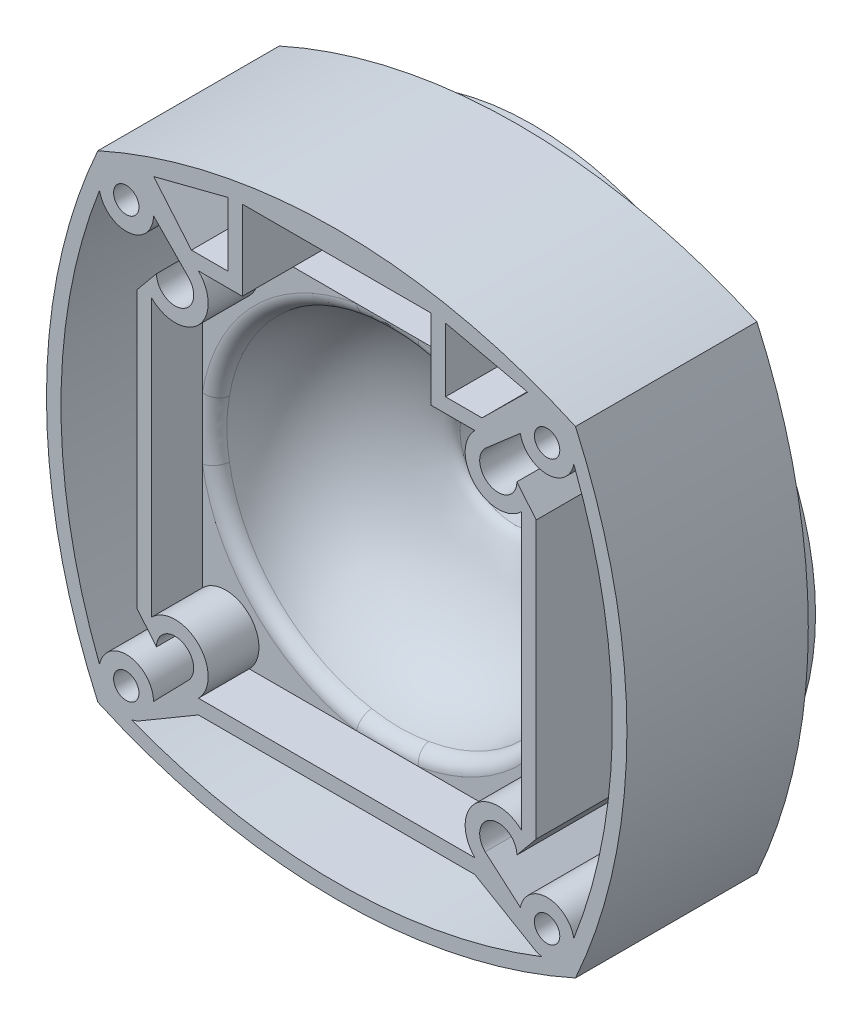
SolidWorks part; units mm, degrees
ref_plane "前视基准面" through (0, 0, 0) normal (0, 0, 1) x (1, 0, 0)
ref_plane "上视基准面" through (0, 0, 0) normal (0, 1, 0) x (1, 0, 0)
ref_plane "右视基准面" through (0, 0, 0) normal (1, 0, 0) x (0, 0, -1)
sketch "草图2" plane through (0, 0, 0) normal (0, 0, 1) x (1, 0, 0)
  line L0 (25.5, 25.5) -> (-25.5, 25.5)
  line L1 (-25.5, 25.5) -> (-25.5, -25.5)
  line L2 (-25.5, -25.5) -> (25.5, -25.5)
  line L3 (25.5, -25.5) -> (25.5, 25.5)
  circle A0 centre (29, -29) radius 1.4
  circle A1 centre (-29, 29) radius 1.4
  circle A2 centre (29, 29) radius 1.4
  circle A3 centre (-29, -29) radius 1.4
  circle A4 centre (-22.2739, -22.2739) radius 3
  circle A5 centre (22.2739, -22.2739) radius 3
  circle A6 centre (-22.2739, 22.2739) radius 3
  circle A7 centre (22.2739, 22.2739) radius 3
  circle A8 centre (-22.2739, -22.2739) radius 1.75
  circle A9 centre (22.2739, -22.2739) radius 1.75
  circle A10 centre (22.2739, 22.2739) radius 1.75
  circle A11 centre (-22.2739, 22.2739) radius 1.75
  arc A12 (32.915, 32.915) -> (-32.915, 32.915) centre (0, -40) ccw
  arc A13 (32.915, -32.915) -> (32.915, 32.915) centre (-40, 0) ccw
  arc A14 (-32.915, -32.915) -> (32.915, -32.915) centre (0, 40) ccw
  arc A15 (-32.915, 32.915) -> (-32.915, -32.915) centre (40, 0) ccw
  arc A16 (0, 25.5) -> (25.5, 0) centre (0, 0) ccw
sketch "草图3" plane through (0, 0, 0) normal (0, 0, 1) x (1, 0, 0)
  arc A8 (-32.915, -32.915) -> (32.915, -32.915) centre (0, 40) ccw
  arc A9 (32.915, -32.915) -> (32.915, 32.915) centre (-40, 0) ccw
  arc A10 (32.915, 32.915) -> (-32.915, 32.915) centre (0, -40) ccw
  arc A11 (-32.915, 32.915) -> (-32.915, -32.915) centre (40, 0) ccw
  arc A12 (-32.915, -32.915) -> (32.915, -32.915) centre (0, 40) ccw
  arc A13 (32.915, -32.915) -> (32.915, 32.915) centre (-40, 0) ccw
  arc A14 (32.915, 32.915) -> (-32.915, 32.915) centre (0, -40) ccw
  arc A15 (-32.915, 32.915) -> (-32.915, -32.915) centre (40, 0) ccw
  dimension "D1" = 0
extrude "凸台-拉伸1" add sketch "草图3" along normal blind 25
sketch "草图4" plane through (0, 0, 0) normal (0, 1, 0) x (1, 0, 0)
  line L0 (0, 0) -> (0, -50000) construction
  line L1 (-32.915, 0) -> (32.915, 0) construction
  line L2 (0, 0) -> (7.5, 0)
  line L3 (0, -18) -> (24, -18)
  line L5 (0, -18) -> (0, 0)
  line L6 (-32.915, -25) -> (32.915, -25) construction
  line L7 (7.5, 0) -> (7.5, -0.5)
  spline S0 degree 3 poles (24, -18) (23.8657, -12.9165) (19.8494, -5.3499) (10.1514, -2.3556) (8.0632, -1.4096) (7.5337, -0.888) (7.5, -0.5) knots 0 0 0 0 0.443597 0.828919 0.884559 1 1 1 1
  point P4 (0, 0)
  dimension "D1" = 7.5
  dimension "D2" = 24
  dimension "D3" = 7
  dimension "D4" = 0.5
revolve "切除-旋转1" cut sketch "草图4" angle 360 about L0
sketch "草图5" plane through (0, 0, 25) normal (0, 0, 1) x (1, 0, 0)
  line L1 (-25.5, 25.5) -> (25.5, 25.5)
  line L2 (-25.5, 25.5) -> (-25.5, -25.5)
  line L3 (-25.5, -25.5) -> (25.5, -25.5)
  line L4 (25.5, 25.5) -> (25.5, -25.5)
extrude "切除-拉伸1" cut sketch "草图5" against normal blind 7
fillet "圆角1" radius 2 1 edges at (-24, 0, 18)
sketch "草图6" plane through (0, 0, 0) normal (0, 0, -1) x (-1, 0, 0)
  circle A0 centre (29, 29) radius 3
  circle A1 centre (-29, 29) radius 3
  circle A2 centre (-29, -29) radius 3
  circle A3 centre (29, -29) radius 3
  dimension "D1" = 6
extrude "切除-拉伸2" cut sketch "草图6" against normal blind 2
sketch "草图7" plane through (0, 0, 2) normal (0, 0, -1) x (-1, 0, 0)
  circle A0 centre (29, 29) radius 1.75
  circle A1 centre (29, -29) radius 1.75
  circle A2 centre (-29, 29) radius 1.75
  circle A3 centre (-29, -29) radius 1.75
  dimension "D1" = 3.5
extrude "切除-拉伸3" cut sketch "草图7" against normal blind 43
sketch "草图8" plane through (0, 0, 18) normal (0, 0, 1) x (1, 0, 0)
  circle A0 centre (-22.2739, -22.2739) radius 4.5624
  circle A1 centre (22.2739, 22.2739) radius 4.5624
extrude "凸台-拉伸2" add sketch "草图8" along normal up to surface (7 mm away) up to face at (-27.25, -29, 25)
sketch "草图9" plane through (0, 0, 18) normal (0, 0, 1) x (1, 0, 0)
  circle A0 centre (22.2739, -22.2739) radius 4.5624
  circle A1 centre (-22.2739, 22.2739) radius 4.5624
extrude "凸台-拉伸3" add sketch "草图9" along normal up to surface (7 mm away) up to face at (-27.25, -29, 25)
sketch "草图10" plane through (0, 0, 0) normal (0, 0, -1) x (-1, 0, 0)
  circle A0 centre (0, 0) radius 11
  dimension "D1" = 22
extrude "凸台-拉伸4" add sketch "草图10" along normal blind 20
sketch "草图11" plane through (0, 0, -20) normal (0, 0, -1) x (-1, 0, 0)
  circle A0 centre (0, 0) radius 7.5
extrude "切除-拉伸4" cut sketch "草图11" against normal blind 54
sketch "草图13" plane through (0, 0, 0) normal (0, 0, -1) x (-1, 0, 0)
  line L0 (0, 0) -> (-49208.2001, 8863.0154) construction
  line L1 (0, 0) -> (-34030.5375, 36632.2606) construction
  line L2 (0, 0) -> (8863.0154, 49208.2001) construction
  line L3 (0, 0) -> (36632.2606, 34030.5375) construction
  line L4 (-17.715, 3.1907) -> (-14.7625, 2.6589)
  line L5 (-12.251, 13.1876) -> (-10.2092, 10.9897)
  line L6 (10.2092, -10.9897) -> (12.251, -13.1876)
  line L7 (14.7625, -2.6589) -> (17.715, -3.1907)
  line L8 (2.6589, 14.7625) -> (3.1907, 17.715)
  line L9 (10.9897, 10.2092) -> (13.1876, 12.251)
  line L10 (-3.1907, -17.715) -> (-2.6589, -14.7625)
  line L11 (-13.1876, -12.251) -> (-10.9897, -10.2092)
  arc A0 (-17.715, 3.1907) -> (-13.1876, -12.251) centre (0, 0) ccw
  arc A1 (-14.7625, 2.6589) -> (-10.9897, -10.2092) centre (0, 0) ccw
  circle A2 centre (0, 0) radius 11 construction
  arc A3 (17.715, -3.1907) -> (13.1876, 12.251) centre (0, 0) ccw
  arc A4 (14.7625, -2.6589) -> (10.9897, 10.2092) centre (0, 0) ccw
  arc A5 (2.6589, 14.7625) -> (-10.2092, 10.9897) centre (0, 0) ccw
  arc A6 (3.1907, 17.715) -> (-12.251, 13.1876) centre (0, 0) ccw
  arc A7 (-3.1907, -17.715) -> (12.251, -13.1876) centre (0, 0) ccw
  arc A8 (-2.6589, -14.7625) -> (10.2092, -10.9897) centre (0, 0) ccw
  dimension "D1" = 3
  dimension "D2" = 4
extrude "凸台-拉伸5" add sketch "草图13" along normal blind 15
sketch "草图14" plane through (0, 0, 0) normal (0, 0, -1) x (-1, 0, 0)
  line L0 (0.6319, -1.5445) -> (18932.2741, -46278.8923) construction
  line L1 (0, 0) -> (41074.2951, -28511.4413) construction
  line L2 (0, 0) -> (-28511.4413, -41074.2951) construction
  line L3 (0, 0) -> (46277.3478, 18931.6423) construction
  line L4 (9.4658, -23.1387) -> (8.3299, -20.362)
  line L5 (20.5137, -14.2894) -> (18.0727, -12.545)
  line L6 (-20.5371, 14.2557) -> (-18.0727, 12.545)
  line L7 (-8.3299, 20.362) -> (-9.4658, 23.1387)
  line L8 (-14.2557, -20.5371) -> (-12.545, -18.0727)
  line L9 (-23.1192, -9.5132) -> (-20.362, -8.3299)
  line L10 (20.362, 8.3299) -> (23.1387, 9.4658)
  line L11 (12.5505, 18.0689) -> (14.262, 20.5328)
  arc A0 (20.5137, -14.2894) -> (23.1387, 9.4658) centre (0, 0) ccw
  arc A1 (18.0727, -12.545) -> (20.362, 8.3299) centre (0, 0) ccw
  circle A2 centre (0, 0) radius 18 construction
  arc A3 (-18.0727, 12.545) -> (-20.362, -8.3299) centre (0, 0) ccw
  arc A4 (-20.5371, 14.2557) -> (-23.1192, -9.5132) centre (0, 0) ccw
  arc A5 (-14.2557, -20.5371) -> (9.4658, -23.1387) centre (0, 0) ccw
  arc A6 (-12.545, -18.0727) -> (8.3299, -20.362) centre (0, 0) ccw
  arc A7 (12.5505, 18.0689) -> (-8.3299, 20.362) centre (0, 0) ccw
  arc A8 (14.262, 20.5328) -> (-9.4658, 23.1387) centre (0, 0) ccw
  dimension "D1" = 3
  dimension "D2" = 4
extrude "凸台-拉伸6" add sketch "草图14" along normal blind 10
sketch "草图15" plane through (0, 0, 0) normal (0, 0, -1) x (-1, 0, 0)
  line L0 (0, 0) -> (-49831.9637, -4095.7778) construction
  line L1 (0, 0) -> (-4095.7778, 49831.9637) construction
  line L2 (0, 0) -> (-42320.3341, 26626.8534) construction
  line L3 (0, 0) -> (-26626.8534, -42320.3341) construction
  line L4 (-31.8925, -2.6213) -> (-28.9025, -2.3756)
  line L5 (-27.085, 17.0412) -> (-24.5458, 15.4436)
  line L6 (24.5458, -15.4436) -> (27.085, -17.0412)
  line L7 (31.8925, 2.6213) -> (28.9025, 2.3756)
  line L8 (-2.3756, 28.9025) -> (-2.6213, 31.8925)
  line L9 (15.4436, 24.5458) -> (17.0412, 27.085)
  line L10 (2.6213, -31.8925) -> (2.3756, -28.9025)
  line L11 (-17.0412, -27.085) -> (-15.4436, -24.5458)
  arc A0 (2.6213, -31.8925) -> (27.085, -17.0412) centre (0, 0) ccw
  arc A1 (2.3756, -28.9025) -> (24.5458, -15.4436) centre (0, 0) ccw
  circle A2 centre (0, 0) radius 25 construction
  arc A3 (-2.6213, 31.8925) -> (-27.085, 17.0412) centre (0, 0) ccw
  arc A4 (-2.3756, 28.9025) -> (-24.5458, 15.4436) centre (0, 0) ccw
  arc A5 (-28.9025, -2.3756) -> (-15.4436, -24.5458) centre (0, 0) ccw
  arc A6 (-31.8925, -2.6213) -> (-17.0412, -27.085) centre (0, 0) ccw
  arc A7 (28.9025, 2.3756) -> (15.4436, 24.5458) centre (0, 0) ccw
  arc A8 (31.8925, 2.6213) -> (17.0412, 27.085) centre (0, 0) ccw
  dimension "D1" = 3
  dimension "D2" = 4
extrude "凸台-拉伸7" add sketch "草图15" along normal blind 5
sketch "草图16" plane through (0, 0, 0) normal (0, 0, -1) x (-1, 0, 0)
  line L0 (0, 0) -> (42388.6496, 26517.9634) construction
  line L1 (0, 0) -> (-26517.9634, 42388.6496) construction
  line L2 (0, 0) -> (-26800.2617, -42208.9133) construction
  line L3 (0, 0) -> (-42208.9133, 26800.2617) construction
  line L4 (-20.9048, -32.924) -> (-19.2968, -30.3914)
  line L5 (-33.0631, -20.684) -> (-30.5198, -19.0929)
  line L6 (-32.924, 20.9048) -> (-30.3914, 19.2968)
  line L7 (-19.0929, 30.5198) -> (-20.684, 33.0631)
  line L8 (20.684, -33.0631) -> (19.0929, -30.5198)
  line L9 (30.3914, -19.2968) -> (32.924, -20.9048)
  line L10 (30.5198, 19.0929) -> (33.0631, 20.684)
  line L11 (19.0929, 30.5198) -> (20.684, 33.0631)
  arc A0 (-20.9048, -32.924) -> (20.684, -33.0631) centre (0, 0) ccw
  arc A1 (-19.2968, -30.3914) -> (19.0929, -30.5198) centre (0, 0) ccw
  circle A2 centre (0, 0) radius 32 construction
  arc A4 (-30.3914, 19.2968) -> (-30.5198, -19.0929) centre (0, 0) ccw
  arc A5 (-32.924, 20.9048) -> (-33.0631, -20.684) centre (0, 0) ccw
  arc A6 (32.924, -20.9048) -> (33.0631, 20.684) centre (0, 0) ccw
  arc A7 (30.3914, -19.2968) -> (30.5198, 19.0929) centre (0, 0) ccw
  arc A8 (20.684, 33.0631) -> (-20.684, 33.0631) centre (0, 0) ccw
  arc A9 (19.0929, 30.5198) -> (-19.0929, 30.5198) centre (0, 0) ccw
  dimension "D1" = 3
  dimension "D2" = 4
extrude "凸台-拉伸8" add sketch "草图16" along normal blind 2
sketch "草图17" plane through (0, 0, -20) normal (0, 0, -1) x (-1, 0, 0)
  line L0 (0, 0) -> (-2.5934, 10.6899)
  line L1 (0, 0) -> (1.2192, 10.9322)
  arc A0 (1.2192, 10.9322) -> (-2.5934, 10.6899) centre (0, 0) ccw
  dimension "D1" = 20
extrude "切除-拉伸5" cut sketch "草图17" against normal blind 3
pattern_circular "阵列(圆周)1" count 6 over 360 about axis through (0, 0, 0) along (0, 0, 1) of "切除-拉伸5"
sketch "草图18" plane through (0, 0, 25) normal (0, 0, 1) x (1, 0, 0)
  line L0 (19.0477, 25.5) -> (-19.0477, 25.5) construction
  line L1 (13, 36.5) -> (-13, 36.5)
  line L2 (13, 36.5) -> (13, 25.5)
  line L3 (13, 25.5) -> (-13, 25.5)
  line L4 (-13, 36.5) -> (-13, 25.5)
  line L5 (-32.915, 32.915) -> (-13, 31) construction
  line L6 (13, 31) -> (32.915, 32.915) construction
  dimension "D1" = 11
  dimension "D2" = 26
extrude "切除-拉伸6" cut sketch "草图18" against normal offset from surface (20 mm away) 5 up to face at (0, 34.6457, 0)
sketch "草图20" plane through (0, 0, 5) normal (0, 0, 1) x (1, 0, 0)
  line L0 (-3, 33.75) -> (-13, 33.75) construction
  line L1 (-3, 35.5) -> (3, 35.5)
  line L2 (-3, 35.5) -> (-3, 32)
  line L3 (-3, 32) -> (3, 32)
  line L4 (3, 35.5) -> (3, 32)
  line L5 (-13, 36.5) -> (-13, 25.5) construction
  line L6 (3, 33.75) -> (13, 33.75) construction
  line L7 (13, 25.5) -> (13, 36.5) construction
  line L8 (13, 36.5) -> (-13, 36.5) construction
  dimension "D1" = 10
  dimension "D2" = 10
  dimension "D3" = 1
  dimension "D4" = 3.5
extrude "切除-拉伸7" cut sketch "草图20" against normal blind 9
sketch "草图21" plane through (0, 0, 5) normal (0, 0, 1) x (1, 0, 0)
  line L0 (13, 36.5) -> (13, 25.5) construction
  line L1 (-13, 25.5) -> (13, 25.5)
  line L2 (-13, 25.5) -> (-13, 28.5)
  line L3 (-13, 28.5) -> (13, 28.5)
  line L4 (13, 25.5) -> (13, 28.5)
  dimension "D1" = 3
extrude "切除-拉伸8" cut sketch "草图21" against normal blind 2
sketch "草图22" plane through (0, 0, 0) normal (0, 1, 0) x (1, 0, 0)
  line L0 (-32.915, -25) -> (32.915, -25) construction
  line L1 (11.4938, -25) -> (-10.5062, -25)
  line L2 (11.4938, -25) -> (11.4938, -9)
  line L3 (11.4938, -9) -> (-10.5062, -9)
  line L4 (-10.5062, -25) -> (-10.5062, -9)
  dimension "D1" = 22
  dimension "D2" = 16
sketch "草图23" plane through (0, 0, 5) normal (0, 0, 1) x (1, 0, 0)
  line L0 (-10, 31) -> (10, 31) construction
  line L1 (-10, 31) -> (-13, 31) construction
  line L2 (-13, 36.5) -> (-13, 25.5) construction
  line L3 (10, 31) -> (13, 31) construction
  line L4 (13, 25.5) -> (13, 36.5) construction
  circle A0 centre (-10, 31) radius 0.9
  circle A1 centre (10, 31) radius 0.9
  dimension "D2" = 1.8
  dimension "D1" = 20
extrude "切除-拉伸9" cut sketch "草图23" against normal blind 3
sketch "草图25" plane through (0, 0, 25) normal (0, 0, 1) x (1, 0, 0)
  line L0 (24.8363, -22.2739) -> (27.5, -19.0477)
  line L1 (27.5, 19.0477) -> (24.8363, 22.2739)
  line L2 (25.3172, -28.2932) -> (20.4619, -24.0858)
  line L3 (25.3157, 28.3013) -> (20.4619, 24.0858)
  line L4 (-20.4619, -24.0858) -> (-25.25, -29)
  line L5 (27.5, -19.0477) -> (27.5, 19.0477)
  line L6 (27.5, -19.0477) -> (27.5, 19.0477)
  line L7 (-24.8363, -22.2739) -> (-27.5, -19.0477)
  line L8 (-27.5, 19.0477) -> (-27.5, -19.0477)
  line L9 (-27.5, 19.0477) -> (-27.5, -19.0477)
  line L10 (-20.4619, 24.0858) -> (-25.25, 29)
  line L11 (-24.8363, 22.2739) -> (-27.5, 19.0477)
  arc A2 (-20.4619, -24.0858) -> (-24.0858, -20.4619) centre (-22.2739, -22.2739) ccw
  circle A3 centre (29, -29) radius 3.75
  arc A4 (32.6844, -28.3016) -> (25.3172, -28.2932) centre (29, -29) ccw
  arc A5 (-20.4619, -24.0858) -> (-24.8363, -22.2739) centre (-22.2739, -22.2739) ccw
  arc A7 (-24.0858, 20.4619) -> (-20.4619, 24.0858) centre (-22.2739, 22.2739) ccw
  arc A8 (-24.8363, 22.2739) -> (-20.4619, 24.0858) centre (-22.2739, 22.2739) ccw
  circle A12 centre (29, 29) radius 3.75
  arc A13 (25.3157, 28.3013) -> (32.6844, 28.3016) centre (29, 29) ccw
  arc A14 (-31.4004, 31.4004) -> (-31.4004, -31.4004) centre (40, 0) ccw
  arc A15 (-31.4004, -31.4004) -> (31.4004, -31.4004) centre (0, 40) ccw
  arc A16 (31.4004, -31.4004) -> (31.4004, 31.4004) centre (-40, 0) ccw
  arc A17 (31.4004, 31.4004) -> (-31.4004, 31.4004) centre (0, -40) ccw
  arc A18 (-32.6844, 28.3016) -> (-32.6844, -28.3016) centre (40, 0) ccw
  arc A20 (32.6844, -28.3016) -> (32.6844, 28.3016) centre (-40, 0) ccw
  circle A23 centre (-29, 29) radius 3.75
  arc A24 (-32.6844, 28.3016) -> (-25.25, 29) centre (-29, 29) ccw
  circle A26 centre (-29, -29) radius 3.75
  arc A27 (-25.25, -29) -> (-32.6844, -28.3016) centre (-29, -29) ccw
  arc A32 (24.0858, -20.4619) -> (20.4619, -24.0858) centre (22.2739, -22.2739) ccw
  arc A33 (24.8363, -22.2739) -> (20.4619, -24.0858) centre (22.2739, -22.2739) ccw
  arc A35 (20.4619, 24.0858) -> (24.0858, 20.4619) centre (22.2739, 22.2739) ccw
  arc A36 (20.4619, 24.0858) -> (24.8363, 22.2739) centre (22.2739, 22.2739) ccw
  dimension "D1" = 2
  dimension "D2" = 2
  dimension "D3" = 2
  dimension "D4" = 2
  dimension "D5" = 2
  dimension "D6" = 2
  dimension "D7" = 2
  dimension "D8" = 2
  dimension "D9" = 2
  dimension "D10" = 2
  dimension "D11" = 2
extrude "切除-拉伸11" cut sketch "草图25" against normal offset from surface (23 mm away) 2 up to face at (0, 33.75, 0)
sketch "草图26" plane through (0, 0, 25) normal (0, 0, 1) x (1, 0, 0)
  line L0 (19.0477, -27.5) -> (26.83, -32.0584)
  line L1 (-19.0477, -27.5) -> (-26.9363, -32.1311)
  line L2 (-19.0477, -27.5) -> (19.0477, -27.5)
  line L3 (-19.0477, -27.5) -> (19.0477, -27.5)
  circle A2 centre (-29, -29) radius 3.75
  arc A3 (-28.3016, -32.6844) -> (-26.9363, -32.1311) centre (-29, -29) ccw
  arc A6 (-32.0922, -31.0922) -> (32.0922, -31.0922) centre (0, 40) ccw
  arc A7 (-28.3016, -32.6844) -> (28.3016, -32.6844) centre (0, 40) ccw
  circle A9 centre (29, -29) radius 3.75
  arc A10 (26.83, -32.0584) -> (28.3016, -32.6844) centre (29, -29) ccw
  dimension "D1" = 2
  dimension "D2" = 2
  dimension "D3" = 2
  dimension "D4" = 2
extrude "切除-拉伸12" cut sketch "草图26" against normal offset from surface (23 mm away) 2
sketch "草图27" plane through (0, 0, 25) normal (0, 0, 1) x (1, 0, 0)
  line L0 (26.3282, 33.7209) -> (15, 36.3024)
  line L1 (15, 36.3024) -> (15, 27.5)
  line L2 (15, 27.5) -> (20.0305, 27.5)
  line L3 (20.0305, 27.5) -> (26.3282, 33.7209)
  line L4 (-15, 36.3024) -> (-25.2236, 33.6781)
  line L5 (-25.2236, 33.6781) -> (-20.0214, 27.5)
  line L6 (-20.0214, 27.5) -> (-15, 27.5)
  line L7 (-15, 27.5) -> (-15, 36.3024)
  line L8 (13, 25.5) -> (13, 36.5) construction
  line L9 (-13, 36.5) -> (-13, 25.5) construction
  line L10 (-13, 25.5) -> (-19.0477, 25.5) construction
  line L12 (19.0477, 25.5) -> (13, 25.5) construction
  point P10 (13, 31)
  point P15 (-20.0214, 27.0113)
  point P18 (16.0239, 25.5)
  dimension "D1" = 2
  dimension "D2" = 2
  dimension "D3" = 2
  dimension "D4" = 2
extrude "切除-拉伸13" cut sketch "草图27" against normal offset from surface (23 mm away) 2
